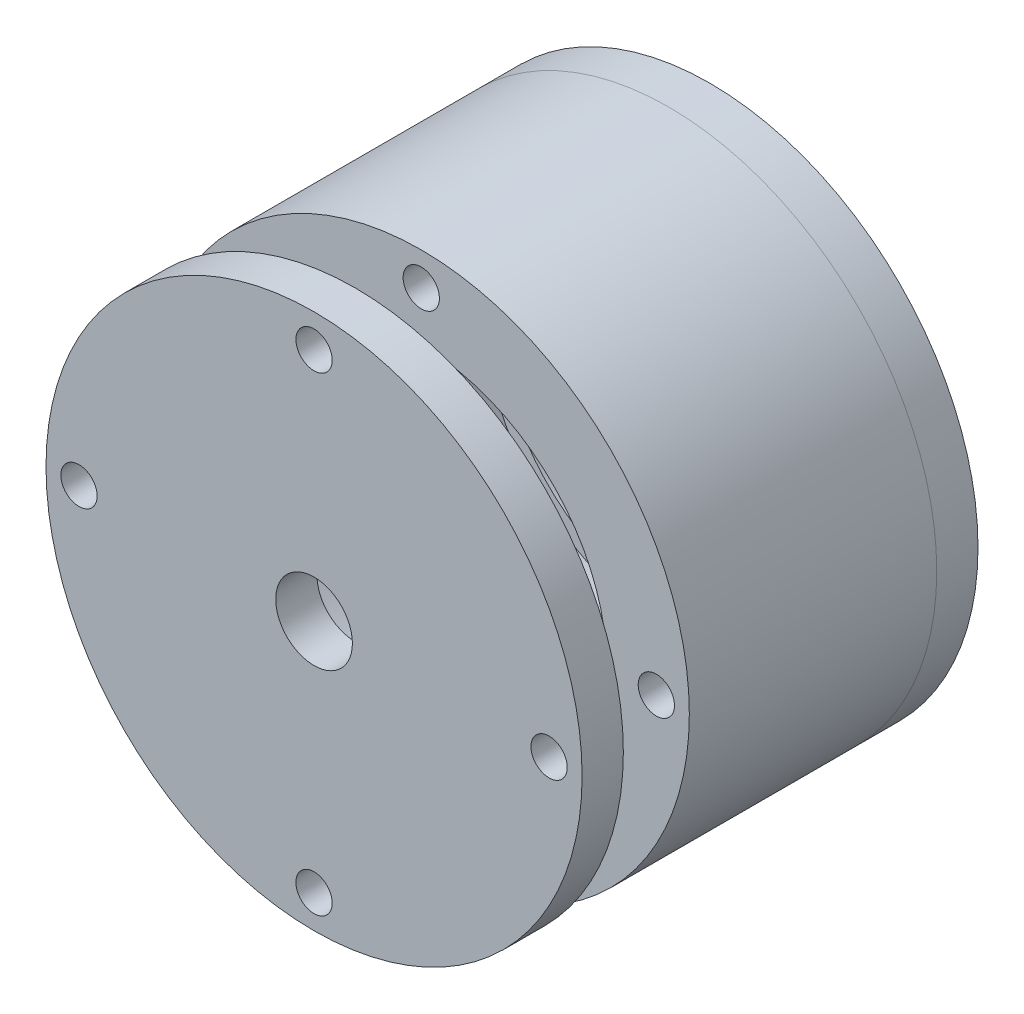
SolidWorks part; units mm, degrees
other "BottomCover"
other "UpCover"
other "Body" parameters "D2"=50.5958, "D3"=50.5958, "D4"=3.8142, "D1"=29.5
ref_plane "Front Plane" through (0, 0, 0) normal (0, 0, 1) x (1, 0, 0)
ref_plane "Top Plane" through (0, 0, 0) normal (0, 1, 0) x (1, 0, 0)
ref_plane "Right Plane" through (0, 0, 0) normal (1, 0, 0) x (0, 0, -1)
sketch "Sketch1" plane through (0, 0, 0) normal (0, 0, 1) x (1, 0, 0)
  line L0 (-32.9906, -34.2) -> (98.1862, -34.2)
  circle A0 centre (-32.9906, -34.2) radius 6.575 construction
  circle A1 centre (-32.9906, -34.2) radius 6.575
  circle A2 centre (-32.9906, -34.2) radius 8.875 construction
  circle A3 centre (-32.9906, -34.2) radius 8.875
sketch "Sketch2" plane through (0, 0, 0) normal (0, 0, 1) x (1, 0, 0)
  line L2 (-58.7906, -34.2) -> (-88.2906, -34.2)
  line L3 (-88.2906, -85) -> (-88.2906, 85) construction
  line L4 (88.2906, -34.2) -> (65.9936, -34.2)
  line L5 (-32.9906, -34.2) -> (98.1862, -34.2) construction
  line L6 (88.2906, 85) -> (88.2906, -85) construction
  circle A1 centre (33.4966, -33.7548) radius 4.65 construction
  circle A2 centre (33.4966, -33.7548) radius 4.65
  circle A3 centre (33.4966, -33.7548) radius 32.5
  circle A5 centre (33.4966, -33.7548) radius 28.5
  circle A6 centre (33.4966, -5.2548) radius 2.2
  circle A7 centre (4.9966, -33.7548) radius 2.2
  circle A8 centre (33.4966, -62.2548) radius 2.2
  circle A9 centre (61.9966, -33.7548) radius 2.2
  circle M40 centre (33.4966, -33.7548) radius 20.6
  circle M41 centre (33.4966, -6.2548) radius 2.2
  circle M42 centre (60.9966, -33.7548) radius 2.2
  circle M43 centre (33.4966, -61.2548) radius 2.2
  circle M44 centre (5.9966, -33.7548) radius 2.2
  dimension "D2" = 57
  dimension "D4" = 4.4
  dimension "D3" = 65
  dimension "D1" = 29.5
extrude "Boss-Extrude1" add sketch "Sketch2" along normal blind 5 contours A3 A2 | A3 A9 A5 A8 A7 A6 | A5 M42 M41 M44 M43 M40 | A9 M42 | A6 M41 | A7 M44 | A8 M43
sketch "Sketch3" plane through (0, 0, 0) normal (0, 0, -1) x (-1, 0, 0)
  line L0 (-5.9966, -33.7548) -> (-0.9966, -33.7548)
  line L1 (-5.9966, -33.7548) -> (-10.9966, -33.7548)
  circle A0 centre (-33.4966, -33.7548) radius 22.5
  circle A1 centre (-33.4966, -33.7548) radius 32.5
  circle A3 centre (-33.4966, -5.2548) radius 2.2
  circle A5 centre (-4.9966, -33.7548) radius 2.2
  circle A7 centre (-33.4966, -62.2548) radius 2.2
  circle A9 centre (-61.9966, -33.7548) radius 2.2 construction
  circle A11 centre (-61.9966, -33.7548) radius 2.2
  circle A17 centre (-33.4966, -33.7548) radius 32.5
  circle A18 centre (-33.4966, -5.2548) radius 2.2
  circle A19 centre (-4.9966, -33.7548) radius 2.2
  circle A20 centre (-33.4966, -62.2548) radius 2.2
  dimension "D1" = 0
  dimension "D2" = 0
  dimension "D3" = 0
  dimension "D4" = 0
extrude "Boss-Extrude2" add sketch "Sketch3" along normal blind 30 from offset 8 separate body
ref_plane "Plane1" through (0, 0, -19) normal (0, 0, -1) x (-1, 0, 0)
mirror "Mirror1" about plane through (0, 0, -19) normal (0, 0, -1) of bodies 101
sketch "Sketch4" plane through (0, 0, 0) normal (0, 0, -1) x (-1, 0, 0)
  circle A0 centre (-33.4966, -33.7548) radius 4.65 construction
  circle A1 centre (-33.4966, -33.7548) radius 4.65
  circle A2 centre (-33.4966, -33.7548) radius 15.6
  circle A3 centre (-33.4966, -33.7548) radius 20.6
  dimension "D1" = 41.2
  dimension "D2" = 31.2
extrude "Cut-Extrude1" cut sketch "Sketch4" against normal blind 2.5 and the other way offset from surface (8 mm away) 2.5 contours A3 A2
sketch "Sketch5" plane through (0, 0, -38) normal (0, 0, 1) x (1, 0, 0)
  circle A0 centre (33.4966, -33.7548) radius 20.6 construction
  circle A1 centre (33.4966, -33.7548) radius 15.6 construction
  circle A2 centre (33.4966, -33.7548) radius 20.6
  circle A3 centre (33.4966, -33.7548) radius 15.6
extrude "Cut-Extrude2" cut sketch "Sketch5" against normal blind 2.5
equation "\"D2@Sketch2\"=\"D3@Sketch2\"-8"
